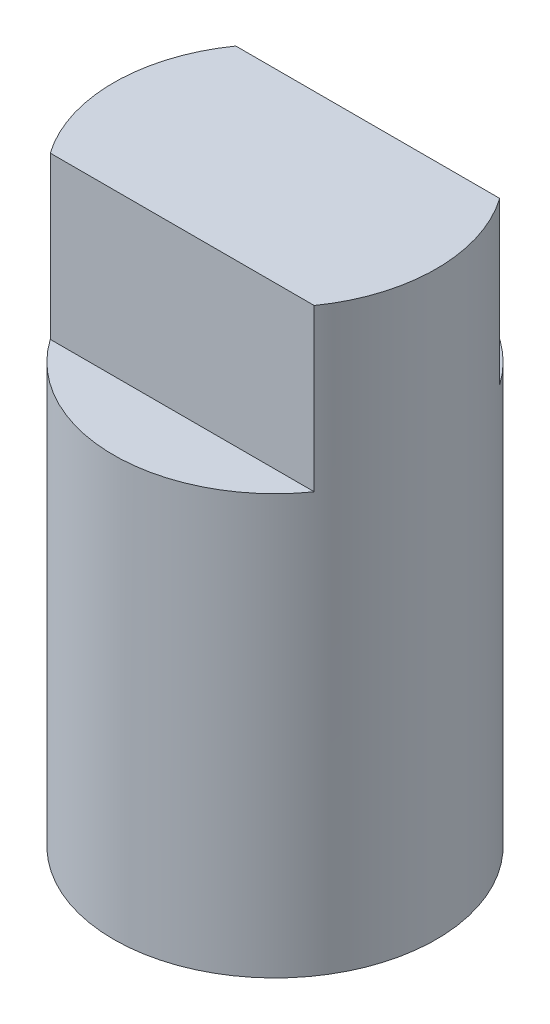
SolidWorks part; units mm, degrees
ref_plane "Front Plane" through (0, 0, 0) normal (0, 0, 1) x (1, 0, 0)
ref_plane "Top Plane" through (0, 0, 0) normal (0, 1, 0) x (1, 0, 0)
ref_plane "Right Plane" through (0, 0, 0) normal (1, 0, 0) x (0, 0, -1)
sketch "Sketch1" plane through (0, 0, 0) normal (0, 1, 0) x (1, 0, 0)
  circle A0 centre (0, 0) radius 25.4
  dimension "D1" = 50.8
extrude "Boss-Extrude1" add sketch "Sketch1" along normal blind 91.44
ref_plane "Plane1" through (25.4, 0, 0) normal (1, 0, 0) x (0, 0, -1)
sketch "Sketch2" plane through (25.4, 0, 0) normal (1, 0, 0) x (0, 0, -1)
  line L0 (25.4, 91.44) -> (-25.4, 91.44) construction
  line L1 (-14.605, 91.44) -> (-25.4, 91.44)
  line L2 (-14.605, 91.44) -> (-14.605, 66.04)
  line L3 (-14.605, 66.04) -> (-25.4, 66.04)
  line L4 (-25.4, 91.44) -> (-25.4, 66.04)
  line L5 (25.4, 0) -> (25.4, 91.44) construction
  line L6 (14.605, 91.44) -> (25.4, 91.44)
  line L7 (14.605, 91.44) -> (14.605, 66.04)
  line L8 (14.605, 66.04) -> (25.4, 66.04)
  line L9 (25.4, 91.44) -> (25.4, 66.04)
  line L10 (-25.4, 91.44) -> (-25.4, 0) construction
  dimension "D1" = 29.21
  dimension "D2" = 25.4
extrude "Cut-Extrude1" cut sketch "Sketch2" against normal up to next
